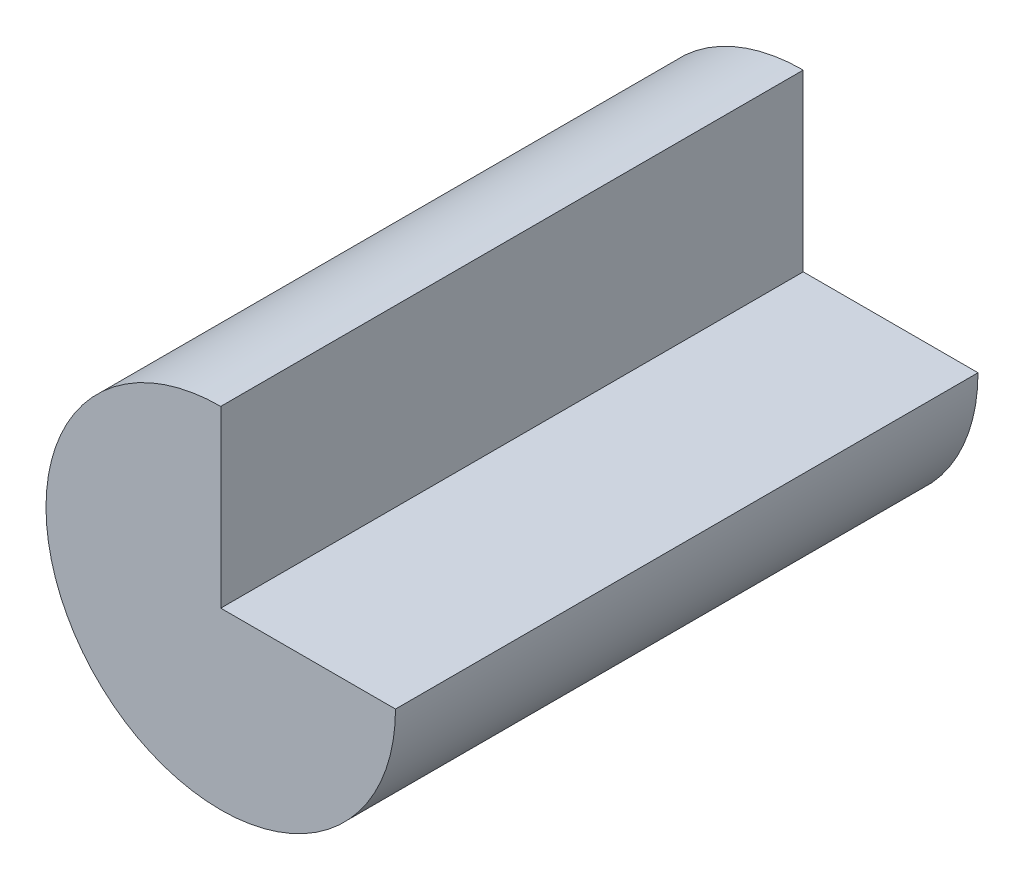
SolidWorks part; units mm, degrees
material "AISI 1020"
ref_plane "Front Plane" through (0, 0, 0) normal (0, 0, 1) x (1, 0, 0)
ref_plane "Top Plane" through (0, 0, 0) normal (0, 1, 0) x (1, 0, 0)
ref_plane "Right Plane" through (0, 0, 0) normal (1, 0, 0) x (0, 0, -1)
sketch "Sketch1" plane through (0, 0, 0) normal (0, 0, 1) x (1, 0, 0)
  circle A0 centre (0, 0) radius 150
  dimension "D1" = 300
extrude "Boss-Extrude1" add sketch "Sketch1" against normal blind 500
sketch "Sketch2" plane through (0, 0, 0) normal (0, 0, 1) x (1, 0, 0)
  line L1 (0, 0) -> (150, 0)
  line L2 (0, 0) -> (0, 150)
  line L3 (0, 150) -> (150, 150)
  line L4 (150, 0) -> (150, 150)
  circle A0 centre (0, 0) radius 150 construction
extrude "Cut-Extrude1" cut sketch "Sketch2" against normal through all
